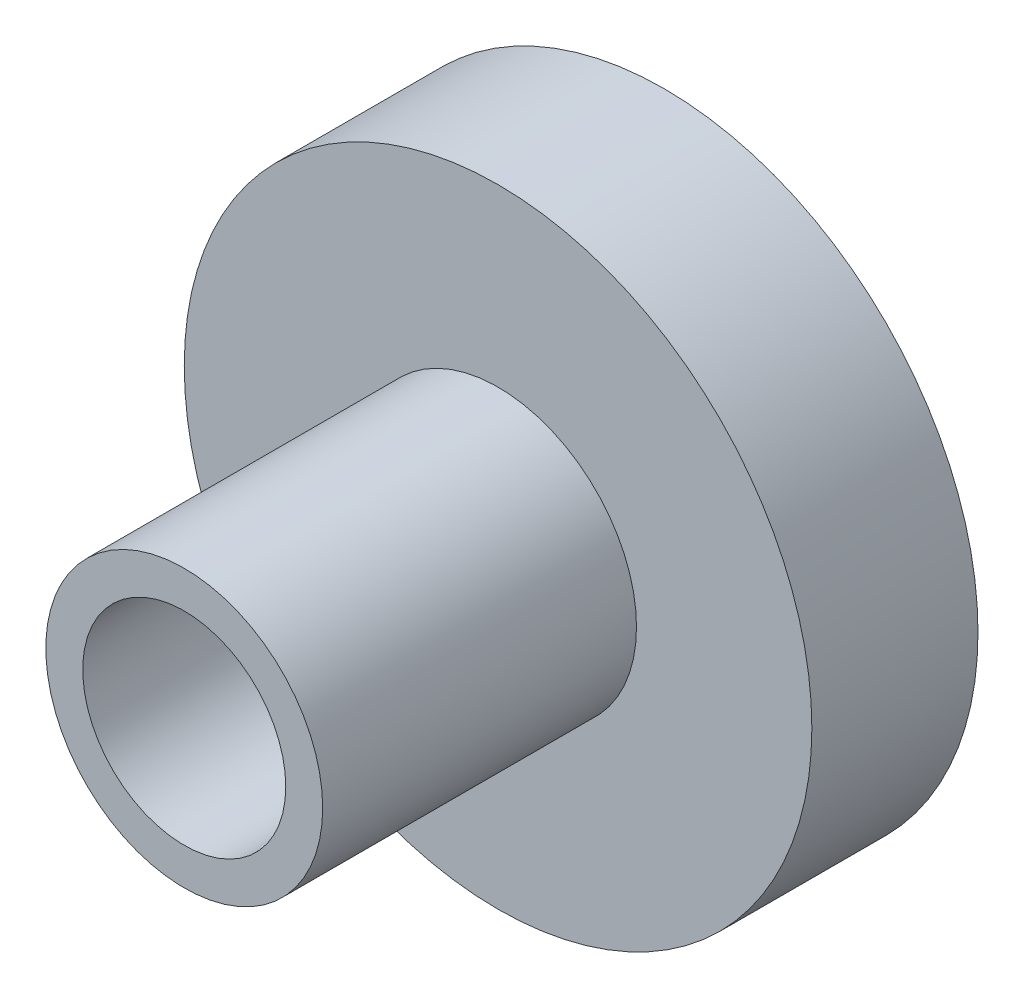
SolidWorks part; units mm, degrees
material "Настроенная пользователем пластмасса"
ref_plane "Спереди" through (0, 0, 0) normal (0, 0, 1) x (1, 0, 0)
ref_plane "Сверху" through (0, 0, 0) normal (0, 1, 0) x (1, 0, 0)
ref_plane "Справа" through (0, 0, 0) normal (1, 0, 0) x (0, 0, -1)
sketch "Эскиз1" plane through (0, 0, 0) normal (0, 1, 0) x (1, 0, 0)
  line L0 (2.75, -13) -> (3.75, -13)
  line L1 (3.75, -13) -> (3.75, -4.5)
  line L2 (3.75, -4.5) -> (8.5, -4.5)
  line L3 (8.5, -4.5) -> (8.5, 0)
  line L4 (8.5, 0) -> (2.75, 0)
  line L5 (2.75, 0) -> (2.75, -13)
  line L6 (0, 0) -> (0, -13) construction
revolve "Повернуть1" add sketch "Эскиз1" angle 360 about L6
